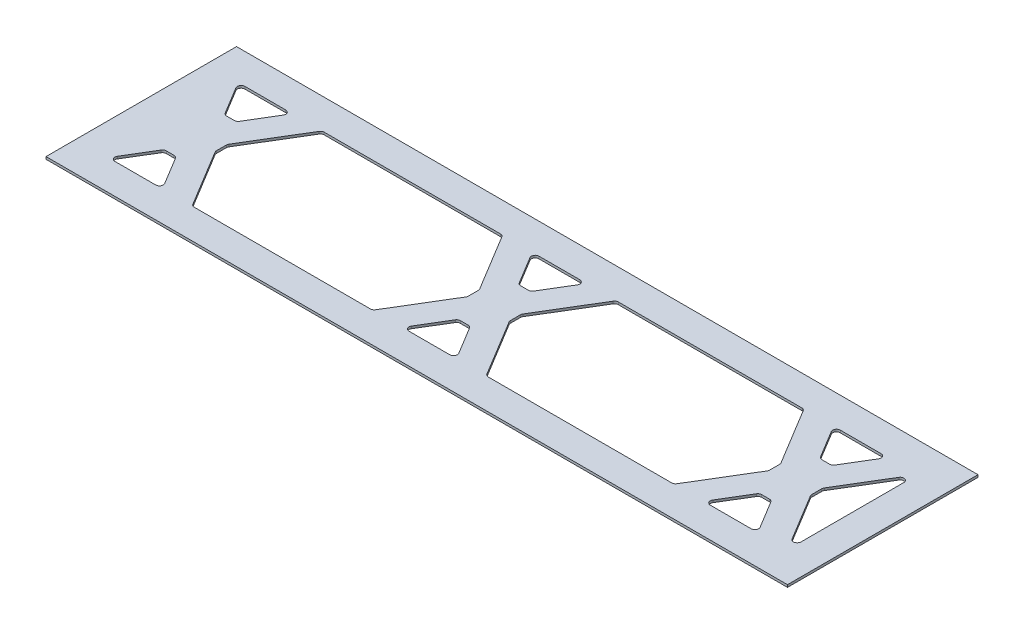
SolidWorks part; units mm, degrees
ref_plane "Front Plane" through (0, 0, 0) normal (0, 0, 1) x (1, 0, 0)
ref_plane "Top Plane" through (0, 0, 0) normal (0, 1, 0) x (1, 0, 0)
ref_plane "Right Plane" through (0, 0, 0) normal (1, 0, 0) x (0, 0, -1)
sketch "Sketch1" plane through (0, 0, 0) normal (0, 1, 0) x (1, 0, 0)
  line L0 (16.2179, 67.2482) -> (33.3428, 67.2482)
  line L1 (49.5062, 67.2482) -> (123.4565, 67.2482)
  line L2 (266.0563, 67.2482) -> (283.1813, 67.2482)
  line L3 (16.2179, 12.7) -> (33.3428, 12.7)
  line L4 (139.6199, 67.2482) -> (156.7448, 67.2482)
  line L5 (298.45, 61.5606) -> (298.45, 18.3876)
  line L6 (265.7683, 37.8885) -> (265.7683, 42.0597)
  line L7 (265.5388, 37.0663) -> (251.251, 13.4654)
  line L8 (139.3318, 42.0597) -> (139.3318, 37.8885)
  line L9 (146.5483, 27.3196) -> (149.8164, 27.3196)
  line L10 (151.1744, 53.394) -> (158.1028, 64.8386)
  line L11 (157.2624, 42.8819) -> (171.5502, 66.4828)
  line L12 (139.1023, 42.8819) -> (124.8145, 66.4828)
  line L13 (145.1903, 53.394) -> (138.2618, 64.8386)
  line L14 (157.2624, 37.0663) -> (171.5502, 13.4654)
  line L15 (151.1744, 26.5542) -> (158.1028, 15.1096)
  line L16 (139.1023, 37.0663) -> (124.8145, 13.4654)
  line L17 (145.1903, 26.5542) -> (138.2618, 15.1096)
  line L18 (157.0329, 37.8885) -> (157.0329, 42.0597)
  line L19 (149.8164, 52.6286) -> (146.5483, 52.6286)
  line L20 (271.6267, 26.5542) -> (264.6983, 15.1096)
  line L21 (277.6109, 26.5542) -> (284.5393, 15.1096)
  line L22 (276.2529, 27.3196) -> (272.9848, 27.3196)
  line L23 (283.6988, 37.0663) -> (295.5045, 17.5655)
  line L24 (283.4694, 42.0597) -> (283.4694, 37.8885)
  line L25 (283.6988, 42.8819) -> (295.5045, 62.3827)
  line L26 (277.6109, 53.394) -> (284.5393, 64.8386)
  line L27 (272.9848, 52.6286) -> (276.2529, 52.6286)
  line L28 (271.6267, 53.394) -> (264.6983, 64.8386)
  line L29 (265.5388, 42.8819) -> (251.251, 66.4828)
  line L30 (23.1463, 52.6286) -> (26.4144, 52.6286)
  line L31 (21.7883, 53.394) -> (14.8598, 64.8386)
  line L32 (172.9082, 67.2482) -> (249.8929, 67.2482)
  line L33 (21.7883, 26.5542) -> (14.8598, 15.1096)
  line L34 (26.4144, 27.3196) -> (23.1463, 27.3196)
  line L35 (27.7724, 26.5542) -> (34.7009, 15.1096)
  line L36 (33.8604, 37.0663) -> (48.1482, 13.4654)
  line L37 (33.6309, 42.0597) -> (33.6309, 37.8885)
  line L38 (33.8604, 42.8819) -> (48.1482, 66.4828)
  line L39 (27.7724, 53.394) -> (34.7009, 64.8386)
  line L40 (49.5062, 12.7) -> (123.4565, 12.7)
  line L41 (139.6199, 12.7) -> (156.7448, 12.7)
  line L42 (172.9082, 12.7) -> (249.8929, 12.7)
  line L43 (266.0563, 12.7) -> (283.1813, 12.7)
  line L45 (0, 79.9482) -> (311.15, 79.9482)
  line L46 (0, 79.9482) -> (0, 0)
  line L47 (0, 0) -> (311.15, 0)
  line L48 (311.15, 79.9482) -> (311.15, 0)
  arc A0 (283.6988, 42.8819) -> (283.4694, 42.0597) centre (285.0569, 42.0597) ccw
  arc A1 (283.4694, 37.8885) -> (283.6988, 37.0663) centre (285.0569, 37.8885) ccw
  arc A2 (295.5045, 17.5655) -> (298.45, 18.3876) centre (296.8625, 18.3876) ccw
  arc A3 (298.45, 61.5606) -> (295.5045, 62.3827) centre (296.8625, 61.5606) ccw
  arc A4 (277.6109, 26.5542) -> (276.2529, 27.3196) centre (276.2529, 25.7321) ccw
  arc A5 (283.1813, 12.7) -> (284.5393, 15.1096) centre (283.1813, 14.2875) ccw
  arc A6 (266.0563, 12.7) -> (264.6983, 15.1096) centre (266.0563, 14.2875) cw
  arc A7 (271.6267, 26.5542) -> (272.9848, 27.3196) centre (272.9848, 25.7321) cw
  arc A8 (272.9848, 52.6286) -> (271.6267, 53.394) centre (272.9848, 54.2161) cw
  arc A9 (276.2529, 52.6286) -> (277.6109, 53.394) centre (276.2529, 54.2161) ccw
  arc A10 (284.5393, 64.8386) -> (283.1813, 67.2482) centre (283.1813, 65.6607) ccw
  arc A11 (266.0563, 67.2482) -> (264.6983, 64.8386) centre (266.0563, 65.6607) ccw
  arc A12 (249.8929, 67.2482) -> (251.251, 66.4828) centre (249.8929, 65.6607) cw
  arc A13 (265.5388, 42.8819) -> (265.7683, 42.0597) centre (264.1808, 42.0597) cw
  arc A14 (265.7683, 37.8885) -> (265.5388, 37.0663) centre (264.1808, 37.8885) cw
  arc A15 (251.251, 13.4654) -> (249.8929, 12.7) centre (249.8929, 14.2875) cw
  arc A16 (172.9082, 12.7) -> (171.5502, 13.4654) centre (172.9082, 14.2875) cw
  arc A17 (157.2624, 37.0663) -> (157.0329, 37.8885) centre (158.6204, 37.8885) cw
  arc A18 (157.0329, 42.0597) -> (157.2624, 42.8819) centre (158.6204, 42.0597) cw
  arc A19 (172.9082, 67.2482) -> (171.5502, 66.4828) centre (172.9082, 65.6607) ccw
  arc A20 (146.5483, 52.6286) -> (145.1903, 53.394) centre (146.5483, 54.2161) cw
  arc A21 (149.8164, 52.6286) -> (151.1744, 53.394) centre (149.8164, 54.2161) ccw
  arc A22 (158.1028, 64.8386) -> (156.7448, 67.2482) centre (156.7448, 65.6607) ccw
  arc A23 (139.6199, 67.2482) -> (138.2618, 64.8386) centre (139.6199, 65.6607) ccw
  arc A24 (151.1744, 26.5542) -> (149.8164, 27.3196) centre (149.8164, 25.7321) ccw
  arc A25 (146.5483, 27.3196) -> (145.1903, 26.5542) centre (146.5483, 25.7321) ccw
  arc A26 (158.1028, 15.1096) -> (156.7448, 12.7) centre (156.7448, 14.2875) cw
  arc A27 (139.6199, 12.7) -> (138.2618, 15.1096) centre (139.6199, 14.2875) cw
  arc A28 (124.8145, 13.4654) -> (123.4565, 12.7) centre (123.4565, 14.2875) cw
  arc A29 (139.1023, 37.0663) -> (139.3318, 37.8885) centre (137.7443, 37.8885) ccw
  arc A30 (139.3318, 42.0597) -> (139.1023, 42.8819) centre (137.7443, 42.0597) ccw
  arc A31 (124.8145, 66.4828) -> (123.4565, 67.2482) centre (123.4565, 65.6607) ccw
  arc A32 (49.5062, 67.2482) -> (48.1482, 66.4828) centre (49.5062, 65.6607) ccw
  arc A33 (33.6309, 42.0597) -> (33.8604, 42.8819) centre (35.2184, 42.0597) cw
  arc A34 (33.8604, 37.0663) -> (33.6309, 37.8885) centre (35.2184, 37.8885) cw
  arc A35 (49.5062, 12.7) -> (48.1482, 13.4654) centre (49.5062, 14.2875) cw
  arc A36 (16.2179, 12.7) -> (14.8598, 15.1096) centre (16.2179, 14.2875) cw
  arc A37 (33.3428, 12.7) -> (34.7009, 15.1096) centre (33.3428, 14.2875) ccw
  arc A38 (27.7724, 26.5542) -> (26.4144, 27.3196) centre (26.4144, 25.7321) ccw
  arc A39 (23.1463, 27.3196) -> (21.7883, 26.5542) centre (23.1463, 25.7321) ccw
  arc A40 (23.1463, 52.6286) -> (21.7883, 53.394) centre (23.1463, 54.2161) cw
  arc A41 (26.4144, 52.6286) -> (27.7724, 53.394) centre (26.4144, 54.2161) ccw
  arc A42 (34.7009, 64.8386) -> (33.3428, 67.2482) centre (33.3428, 65.6607) ccw
  arc A43 (14.8598, 64.8386) -> (16.2179, 67.2482) centre (16.2179, 65.6607) cw
  point P7 (150.7111, 52.6286)
  point P8 (157.0329, 42.5028)
  point P88 (157.0329, 42.5028)
  point P95 (150.7111, 52.6286)
  dimension "D5" = 1.5875
  dimension "D1" = 12.7
  dimension "D2" = 12.7
  dimension "D3" = 311.15
  dimension "D4" = 12.7
extrude "Boss-Extrude1" add sketch "Sketch1" along normal blind 1
